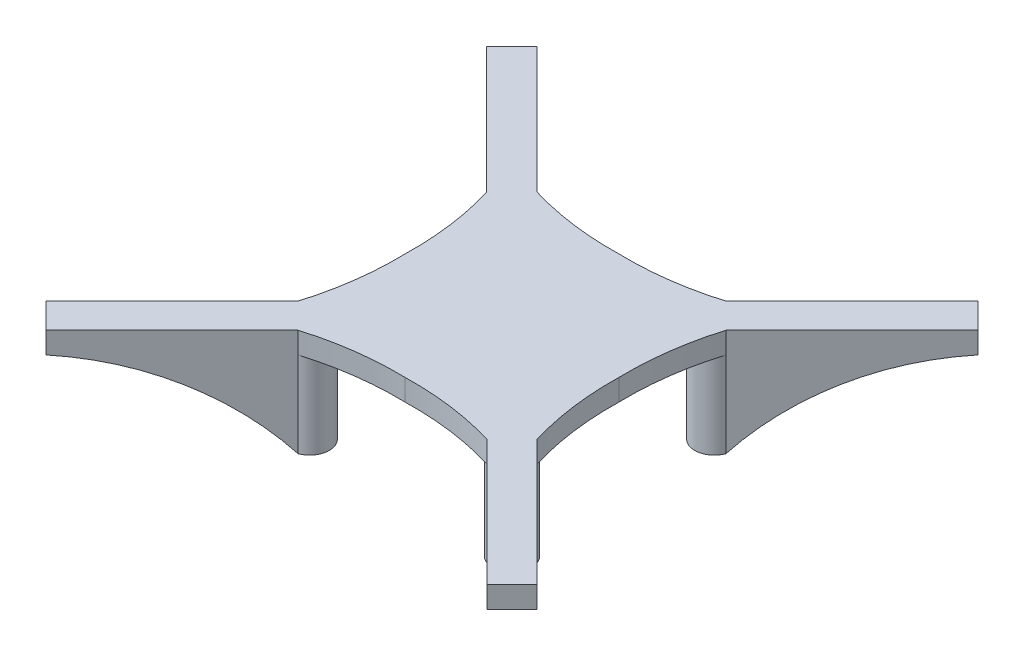
SolidWorks part; units mm, degrees
ref_plane "Přední rovina" through (0, 0, 0) normal (0, 0, 1) x (1, 0, 0)
ref_plane "Horní rovina" through (0, 0, 0) normal (0, 1, 0) x (1, 0, 0)
ref_plane "Pravá rovina" through (0, 0, 0) normal (1, 0, 0) x (0, 0, -1)
sketch "Skica2" plane through (0, 0, 0) normal (0, 1, 0) x (1, 0, 0)
  line L7 (-68.91, 61.8198) -> (-33.5546, 26.4645)
  line L8 (-61.8198, -68.8909) -> (-68.8909, -61.8198)
  line L9 (61.8198, -68.8909) -> (68.8909, -61.8198)
  line L10 (68.8909, 61.8198) -> (61.8198, 68.8909)
  line L11 (-68.91, 61.8198) -> (-61.8389, 68.8909)
  line L14 (-61.8389, 68.8909) -> (-26.4836, 33.5355)
  line L15 (61.8198, 68.8909) -> (26.4645, 33.5355)
  line L16 (68.8909, 61.8198) -> (33.5355, 26.4645)
  line L17 (-68.8909, -61.8198) -> (-33.5355, -26.4645)
  line L18 (-61.8198, -68.8909) -> (-26.4645, -33.5355)
  line L19 (61.8198, -68.8909) -> (26.4645, -33.5355)
  line L20 (68.8909, -61.8198) -> (33.5355, -26.4645)
  arc A0 (-33.5546, 26.4645) -> (-30, 0) centre (-114.9751, 2.0573) cw
  arc A1 (-33.5355, -26.4645) -> (-30, 0) centre (-114.9737, -2.1163) ccw
  arc A2 (-26.4645, -33.5355) -> (0, -30) centre (-2.1163, -114.9737) cw
  arc A3 (26.4645, -33.5355) -> (0, -30) centre (2.1163, -114.9737) ccw
  arc A4 (33.5355, -26.4645) -> (30, 0) centre (114.9737, -2.1163) cw
  arc A5 (33.5355, 26.4645) -> (30, 0) centre (114.9737, 2.1163) ccw
  arc A6 (26.4645, 33.5355) -> (0, 30) centre (2.1163, 114.9737) cw
  arc A7 (-26.4836, 33.5355) -> (0, 30) centre (-2.1339, 114.9732) ccw
  dimension "D15" = 50
  dimension "D3" = 85
  dimension "D4" = 85
  dimension "D5" = 85
  dimension "D6" = 85
  dimension "D7" = 85
  dimension "D8" = 85
  dimension "D9" = 85
  dimension "D12" = 85
  dimension "D10" = 10
  dimension "D11" = 10
  dimension "D13" = 50
  dimension "D16" = 50
  dimension "D17" = 50
  dimension "D18" = 50
  dimension "D19" = 50
  dimension "D20" = 50
  dimension "D21" = 50
extrude "Přidat vysunutím2" add sketch "Skica2" along normal blind 30 contours L7 A0 A1 L17 L8 L18 A2 A3 L19 L9 L20 A4 A5 L16 L10 L15 A6 A7 L14 L11
sketch "Skica4" plane through (3.5355, 0, -3.5355) normal (0.7071, 0, -0.7071) x (-0.7071, 0, -0.7071)
  line L1 (-92.4264, 30) -> (-92.4264, 0) construction
  line L2 (-42.4264, 0) -> (-92.4264, 0)
  line L3 (-92.4264, 0) -> (-92.4264, 24)
  arc A0 (-92.4264, 24) -> (-42.4264, 0) centre (-97.5813, -50.8226) cw
  dimension "D2" = 75
extrude "Odebrat vysunutím1" cut sketch "Skica4" against normal blind 30
sketch "Skica5" plane through (3.5355, 0, 3.5355) normal (0.7071, 0, 0.7071) x (0.7071, 0, -0.7071)
  line L0 (-92.4264, 0) -> (-92.4264, 24)
  line L1 (-92.4264, 30) -> (-92.4264, 0) construction
  line L2 (-42.4264, 0) -> (-92.4264, 0)
  arc A0 (-92.4264, 24) -> (-42.4264, 0) centre (-97.5813, -50.8226) cw
  dimension "D2" = 75
  dimension "D1" = 24
extrude "Odebrat vysunutím2" cut sketch "Skica5" against normal blind 30
sketch "Skica6" plane through (-3.5451, 0, 3.5451) normal (-0.7071, 0, 0.7071) x (0.7071, 0, 0.7071)
  line L0 (-92.4399, 0) -> (-92.4399, 24)
  line L1 (-92.4399, 30) -> (-92.4399, 0) construction
  line L2 (-42.4399, 0) -> (-92.4399, 0)
  arc A0 (-92.4399, 24) -> (-42.4399, 0) centre (-97.5948, -50.8226) cw
  dimension "D2" = 75
  dimension "D1" = 24
extrude "Odebrat vysunutím3" cut sketch "Skica6" against normal blind 30
sketch "Skica7" plane through (-3.5355, 0, -3.5355) normal (-0.7071, 0, -0.7071) x (-0.7071, 0, 0.7071)
  line L0 (-92.4264, 0) -> (-92.4264, 24)
  line L1 (-92.4264, 30) -> (-92.4264, 0) construction
  line L2 (-42.4264, 0) -> (-92.4264, 0)
  arc A0 (-92.4264, 24) -> (-42.4264, 0) centre (-97.5813, -50.8226) cw
  dimension "D2" = 75
  dimension "D1" = 24
extrude "Odebrat vysunutím4" cut sketch "Skica7" against normal blind 30
sketch "Skica8" plane through (0, 0, 0) normal (0, -1, 0) x (1, 0, 0)
  line L0 (-33.5546, -26.4645) -> (-33.5355, 26.4645)
  line L1 (26.4645, 33.5355) -> (-26.4645, 33.5355)
  line L2 (33.5355, 26.4645) -> (33.5355, -26.4645)
  line L3 (26.4645, -33.5355) -> (-26.4836, -33.5355)
  arc A0 (-26.4645, 33.5355) -> (-33.5355, 26.4645) centre (-28.3798, 28.3798) cw
  arc A1 (26.4645, 33.5355) -> (33.5355, 26.4645) centre (28.3798, 28.3798) ccw
  arc A2 (33.5355, -26.4645) -> (26.4645, -33.5355) centre (28.3798, -28.3798) ccw
  arc A3 (-26.4836, -33.5355) -> (-33.5546, -26.4645) centre (-28.3989, -28.3798) ccw
  dimension "D1" = 5.5
  dimension "D2" = 5.5
  dimension "D3" = 5.5
  dimension "D4" = 5.5
extrude "Odebrat vysunutím5" cut sketch "Skica8" against normal blind 24
